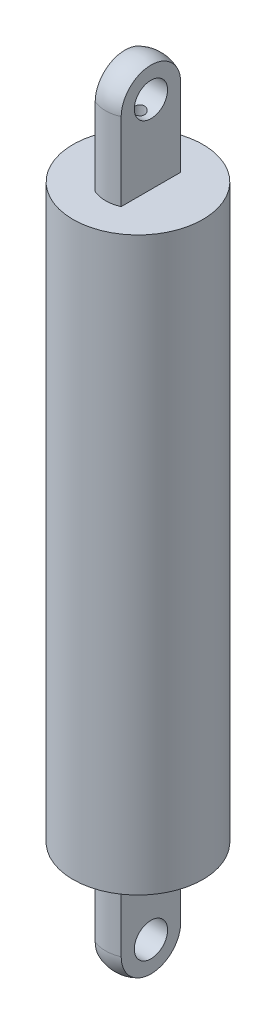
SolidWorks part; units mm, degrees
ref_plane "Front Plane" through (0, 0, 0) normal (0, 0, 1) x (1, 0, 0)
ref_plane "Top Plane" through (0, 0, 0) normal (0, 1, 0) x (1, 0, 0)
ref_plane "Right Plane" through (0, 0, 0) normal (1, 0, 0) x (0, 0, -1)
sketch "Sketch1" plane through (0, 0, 0) normal (1, 0, 0) x (0, 0, -1)
  line L0 (-6.35, 27.94) -> (-6.35, -27.94)
  line L1 (0, 35.56) -> (0, -35.56) construction
  line L2 (-3.175, 35.56) -> (-3.175, 27.94)
  line L3 (-3.175, 27.94) -> (-6.35, 27.94)
  line L4 (0, 38.735) -> (0, 35.56) construction
  line L5 (55, 0) -> (-55, 0) construction
  line L6 (-3.175, -27.94) -> (-6.35, -27.94)
  line L7 (-3.175, -35.56) -> (-3.175, -27.94)
  arc A0 (0, 37.187) -> (0, 33.933) centre (0, 35.56) ccw
  arc A1 (0, 38.735) -> (-3.175, 35.56) centre (0, 35.56) ccw
  arc A2 (0, -38.735) -> (-3.175, -35.56) centre (0, -35.56) cw
  arc A3 (0, -37.187) -> (0, -33.933) centre (0, -35.56) cw
  point P2 (-6.35, 0)
  point P6 (0, 0)
  dimension "D3" = 3.254
  dimension "D4" = 6.35
  dimension "D1" = 71.12
  dimension "D2" = 6.35
  dimension "D5" = 7.62
revolve "Revolve-Thin1" add sketch "Sketch1" angle 360 about L1
sketch "Sketch3" plane through (0, 27.94, 0) normal (0, 1, 0) x (1, 0, 0)
  line L1 (1.27, -3.81) -> (-1.27, -3.81) construction
  line L2 (1.27, -3.81) -> (1.27, 3.81)
  line L3 (1.27, 3.81) -> (-1.27, 3.81) construction
  line L4 (-1.27, -3.81) -> (-1.27, 3.81)
  line L5 (1.27, -3.81) -> (-1.27, 3.81) construction
  line L6 (1.27, 3.81) -> (-1.27, -3.81) construction
  line L7 (-1.27, 3.81) -> (-3.81, 3.81)
  line L8 (-1.27, 3.81) -> (-1.27, -3.81)
  line L9 (-1.27, -3.81) -> (-3.81, -3.81)
  line L10 (-3.81, 3.81) -> (-3.81, -3.81)
  line L11 (1.27, 3.81) -> (3.81, 3.81)
  line L12 (1.27, 3.81) -> (1.27, -3.81)
  line L13 (1.27, -3.81) -> (3.81, -3.81)
  line L14 (3.81, 3.81) -> (3.81, -3.81)
  point P0 (0, 0)
  circle M9 centre (0, 0) radius 3.175
  dimension "D1" = 2.54
  dimension "D2" = 7.62
  dimension "D3" = 2.54
extrude "Cut-Extrude2" cut sketch "Sketch3" along normal through all contours L4 M9 | L2 M9
mirror "Mirror1" about plane through (0, 0, 0) normal (0, 1, 0) of "Cut-Extrude2"
sketch "Sketch4" plane through (1.27, 0, 0) normal (1, 0, 0) x (0, 0, -1)
  line L0 (0, 55) -> (0, -55) construction
  circle A0 centre (0, 35.56) radius 1.627
  circle A1 centre (0, -35.56) radius 1.627
  arc A3 (2.9099, 35.56) -> (-2.9099, 35.56) centre (0, 35.56) ccw construction
  arc A4 (-2.9099, -35.56) -> (2.9099, -35.56) centre (0, -35.56) ccw construction
  dimension "D1" = 3.254
extrude "Cut-Extrude3" cut sketch "Sketch4" against normal through all
